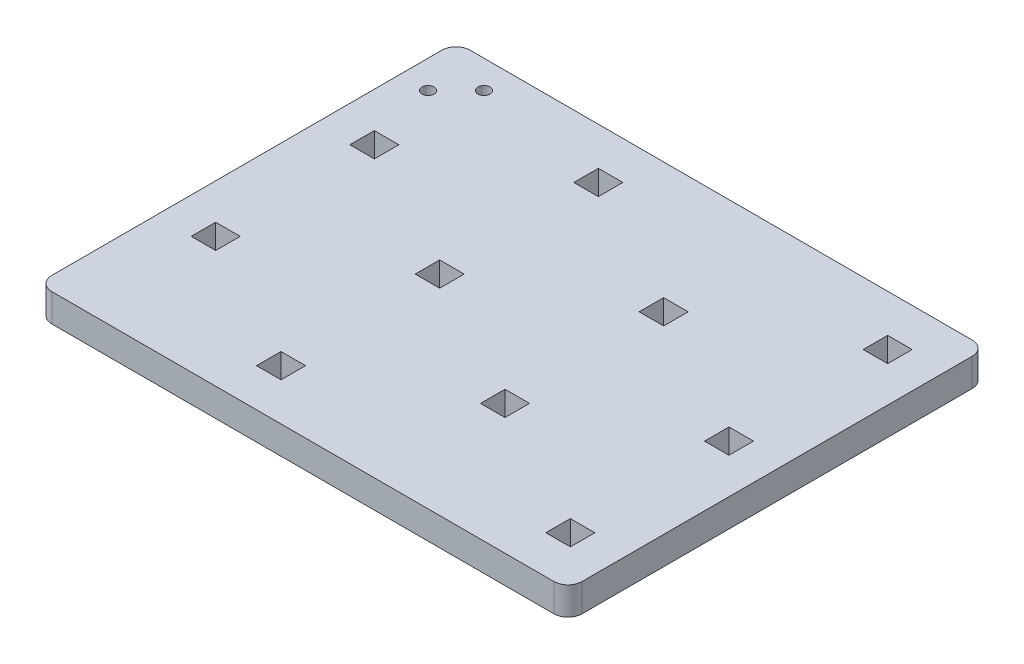
SolidWorks part; units mm, degrees
material "Polyurethane Foam Rigid"
ref_plane "Front Plane" through (0, 0, 0) normal (0, 0, 1) x (1, 0, 0)
ref_plane "Top Plane" through (0, 0, 0) normal (0, 1, 0) x (1, 0, 0)
ref_plane "Right Plane" through (0, 0, 0) normal (1, 0, 0) x (0, 0, -1)
sketch "Sketch1" plane through (0, 0, 0) normal (0, 1, 0) x (1, 0, 0)
  line L1 (0, 0) -> (481.0125, 0)
  line L2 (0, 0) -> (0, 379.4125)
  line L3 (0, 379.4125) -> (481.0125, 379.4125)
  line L4 (481.0125, 0) -> (481.0125, 379.4125)
  dimension "D1" = 379.4125
  dimension "D2" = 481.0125
extrude "Boss-Extrude1" add sketch "Sketch1" along normal blind 25.4
fillet "Fillet1" radius 12.7 4 edges at (0, 12.7, 0) (481.0125, 12.7, 0) (481.0125, 12.7, -379.4125) (0, 12.7, -379.4125)
sketch "Sketch2" plane through (0, 25.4, 0) normal (0, 1, 0) x (1, 0, 0)
  line L0 (437.3563, 189.7062) -> (437.3563, 45.7729) construction
  line L1 (240.5062, 379.4125) -> (240.5062, 0) construction
  line L2 (468.3125, 379.4125) -> (12.7, 379.4125) construction
  line L3 (12.7, 0) -> (468.3125, 0) construction
  line L4 (0, 189.7063) -> (481.0125, 189.7062) construction
  line L5 (0, 366.7125) -> (0, 12.7) construction
  line L6 (481.0125, 12.7) -> (481.0125, 366.7125) construction
  line L7 (306.1229, 117.7396) -> (437.3563, 117.7396) construction
  line L8 (469.1063, 367.5063) -> (11.9063, 367.5063) construction
  line L9 (469.1063, 367.5063) -> (469.1063, 11.9063) construction
  line L10 (469.1063, 11.9063) -> (11.9063, 11.9063) construction
  line L11 (11.9063, 367.5063) -> (11.9063, 11.9063) construction
  line L12 (469.1063, 367.5063) -> (11.9063, 11.9063) construction
  line L13 (469.1063, 11.9063) -> (11.9063, 367.5063) construction
  line L14 (43.6563, 117.7396) -> (306.1229, 117.7396) construction
  line L15 (43.6563, 261.6729) -> (306.1229, 261.6729) construction
  point P12 (240.5062, 189.7062)
  line B0 (32.5438, 128.8521) -> (54.7688, 128.8521)
  line B1 (32.5438, 128.8521) -> (32.5438, 106.6271)
  line B2 (32.5438, 106.6271) -> (54.7688, 106.6271)
  line B3 (54.7688, 128.8521) -> (54.7688, 106.6271)
  line B4 (32.5438, 128.8521) -> (54.7688, 106.6271) construction
  line B5 (32.5438, 106.6271) -> (54.7688, 128.8521) construction
  line B6 (32.5438, 250.5604) -> (54.7688, 250.5604)
  line B7 (32.5438, 250.5604) -> (32.5438, 272.7854)
  line B8 (32.5438, 272.7854) -> (54.7688, 272.7854)
  line B9 (54.7688, 250.5604) -> (54.7688, 272.7854)
  line B10 (163.7771, 56.8854) -> (186.0021, 56.8854)
  line B11 (163.7771, 56.8854) -> (163.7771, 34.6604)
  line B12 (163.7771, 34.6604) -> (186.0021, 34.6604)
  line B13 (186.0021, 56.8854) -> (186.0021, 34.6604)
  line B14 (295.0104, 128.8521) -> (317.2354, 128.8521)
  line B15 (295.0104, 128.8521) -> (295.0104, 106.6271)
  line B16 (295.0104, 106.6271) -> (317.2354, 106.6271)
  line B17 (317.2354, 128.8521) -> (317.2354, 106.6271)
  line B18 (426.2438, 56.8854) -> (448.4688, 56.8854)
  line B19 (426.2438, 56.8854) -> (426.2438, 34.6604)
  line B20 (426.2438, 34.6604) -> (448.4688, 34.6604)
  line B21 (448.4688, 56.8854) -> (448.4688, 34.6604)
  line B22 (426.2438, 200.8187) -> (448.4688, 200.8187)
  line B23 (426.2438, 200.8187) -> (426.2438, 178.5937)
  line B24 (426.2438, 178.5937) -> (448.4688, 178.5937)
  line B25 (448.4688, 200.8187) -> (448.4688, 178.5937)
  line B26 (426.2438, 322.5271) -> (448.4688, 322.5271)
  line B27 (426.2438, 322.5271) -> (426.2438, 344.7521)
  line B28 (426.2438, 344.7521) -> (448.4688, 344.7521)
  line B29 (448.4688, 322.5271) -> (448.4688, 344.7521)
  line B30 (163.7771, 200.8187) -> (186.0021, 200.8187)
  line B31 (163.7771, 200.8187) -> (163.7771, 178.5937)
  line B32 (163.7771, 178.5937) -> (186.0021, 178.5937)
  line B33 (186.0021, 200.8187) -> (186.0021, 178.5937)
  line B34 (163.7771, 344.7521) -> (186.0021, 344.7521)
  line B35 (163.7771, 344.7521) -> (163.7771, 322.5271)
  line B36 (163.7771, 322.5271) -> (186.0021, 322.5271)
  line B37 (186.0021, 344.7521) -> (186.0021, 322.5271)
  line B38 (295.0104, 272.7854) -> (317.2354, 272.7854)
  line B39 (295.0104, 272.7854) -> (295.0104, 250.5604)
  line B40 (295.0104, 250.5604) -> (317.2354, 250.5604)
  line B41 (317.2354, 272.7854) -> (317.2354, 250.5604)
  dimension "D1" = 457.2
  dimension "D2" = 355.6
  dimension "D4" = 31.75
  dimension "D5" = 31.75
  dimension "D6" = 33.8667
  dimension "D7" = 31.75
  dimension "D8" = 162.9833
  dimension "D9" = 162.9833
  dimension "D10" = 33.8667
  dimension "D12" = 162.9833
  dimension "D13" = 33.8667
  dimension "D14" = 162.9833
  dimension "D16" = 162.9833
sketch_block_instance "Block1-1"
sketch_block "Block1" parameters "D1"=22.225, "D2"=22.225
sketch_block_instance "Block1-5"
sketch_block_instance "Block1-7"
sketch_block_instance "Block1-8"
sketch_block_instance "Block1-9"
sketch_block_instance "Block1-10"
sketch_block_instance "Block1-11"
sketch_block_instance "Block1-12"
sketch_block_instance "Block1-13"
sketch_block_instance "Block1-14"
extrude "Cut-Extrude2" cut sketch "Sketch2" against normal blind 25.4
sketch "Sketch3" plane through (0, 25.4, 0) normal (0, 1, 0) x (1, 0, 0)
  line L0 (0, 366.7125) -> (0, 12.7) construction
  line L1 (468.3125, 379.4125) -> (12.7, 379.4125) construction
  circle A0 centre (25.4, 328.6125) radius 5.5563
  circle A1 centre (50.8, 354.0125) radius 5.5563
  dimension "D1" = 11.1125
  dimension "D2" = 11.1125
  dimension "D3" = 25.4
  dimension "D4" = 25.4
  dimension "D5" = 50.8
  dimension "D6" = 50.8
extrude "Cut-Extrude3" cut sketch "Sketch3" against normal blind 25.4
equation "\"2.33333333in-\"=2.33333"
